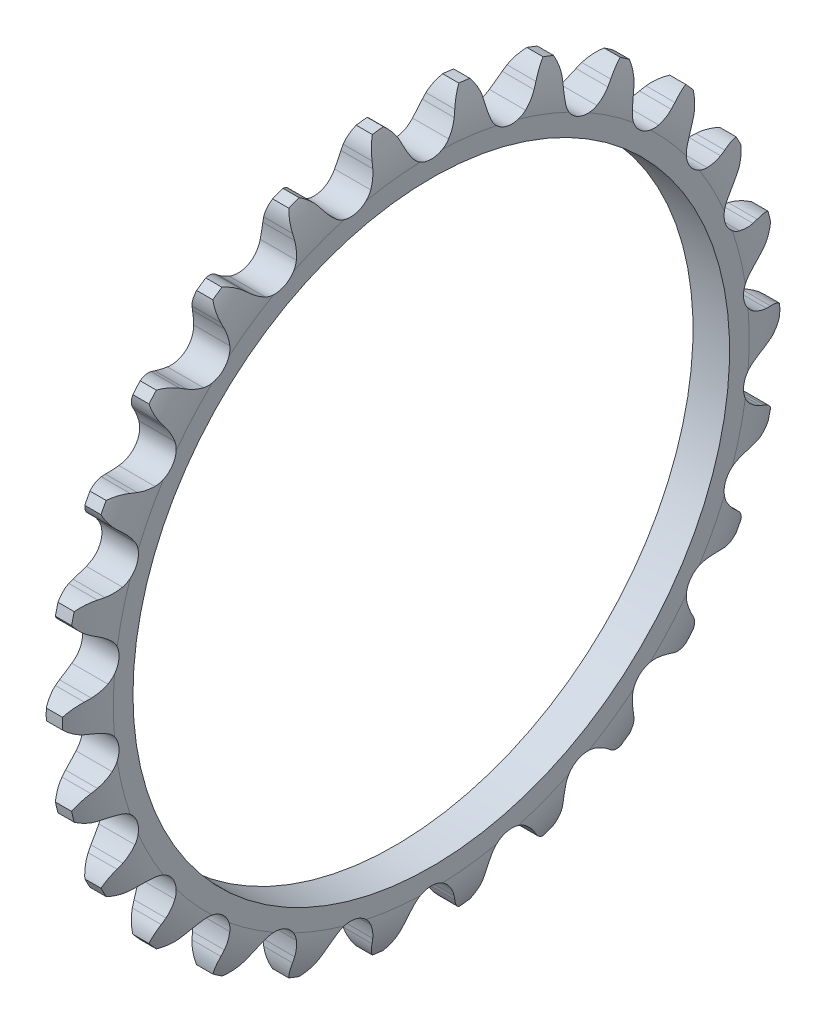
SolidWorks part; units mm, degrees
ref_plane "Plane1" through (0, 0, 0) normal (0, 0, 1) x (1, 0, 0)
ref_plane "Plane2" through (0, 0, 0) normal (0, 1, 0) x (1, 0, 0)
ref_plane "Plane3" through (0, 0, 0) normal (1, 0, 0) x (0, 0, -1)
other "Configuration Table"
sketch "Clipboard" plane through (0, 0, 0) normal (0, 1, 0) x (1, 0, 0)
  line L0 (0, 0) -> (8.561, -4.1755)
  line L1 (-15, 0) -> (100, 0) construction
  line L2 (0, 0) -> (-0.7911, 0.8941)
  line L3 (0, 0) -> (-4.4605, 1.7048)
  line L4 (0, 0) -> (4.2919, 2.0933)
  line L5 (0, 0) -> (-47.5972, -17.7524)
  line L6 (0, 0) -> (-3.555, -2.3986)
  line L7 (-0.7911, 0.8941) -> (44.4721, 23.9568)
  line L8 (-76.2, 38.1) -> (-58.1914, 38.1)
  line L9 (-73.2057, 38.5609) -> (-73.0533, 38.5634)
  line L10 (-73.0533, 76.1892) -> (-62.9187, 76.1892)
  circle A0 centre (0, 0) radius 2.54
  circle A1 centre (0, 0) radius 34.0792
  circle A2 centre (0, 0) radius 38.1
  dimension "Dr" = 5.08
  dimension "MHD" = 68.1584
  dimension "Hub_dia" = 76.2
  dimension "Num_teeth" = 26
  dimension "Pitch" = 9.525
  dimension "Width" = 4.7752
  dimension "Chamfer_wid" = 1.1938
  dimension "Chamfer_dep" = 4.7752
  dimension "Overall_len" = 50.8
  dimension "Show_teeth" = 26
  dimension "Thickness" = 4.2885
  dimension "OAL" = 50.8001
  dimension "T_dim" = 18.0086
  dimension "Width_const" = 0.1524
  dimension "Width_factor" = 0.93
  dimension "Num_strands" = 1
  dimension "Transv_pitch" = 10.1346
sketch "BasProSke" plane through (0, 0, 0) normal (0, 1, 0) x (1, 0, 0)
  line L0 (-10, 0) -> (60, 0) construction
  line L1 (0, 0) -> (0, 37.305)
  line L2 (0, 0) -> (4.2885, 0)
  line L3 (4.2885, 0) -> (4.2885, 37.305)
  line L4 (3.0947, 42.0802) -> (1.1938, 42.0802)
  arc A0 (0, 37.305) -> (1.1938, 42.0802) centre (10.1473, 37.305) cw
  arc A1 (4.2885, 37.305) -> (3.0947, 42.0802) centre (-5.8588, 37.305) ccw
  dimension "Thickness" = 4.2885
  dimension "D1" = 10.1473
  dimension "G1" = 1.1938
  dimension "G2" = 1.1938
  dimension "H2" = 4.7752
  dimension "H1" = 4.7752
  dimension "Diameter" = 84.1604
revolve "Base-Revolve" add sketch "BasProSke" angle 360 about L0
sketch "GrvSke" plane through (0, 0, 0) normal (0, 1, 0) x (1, 0, 0)
  line L0 (4.2885, 37.305) -> (4.2885, 34.0792)
  line L1 (4.2885, 34.0792) -> (10.1346, 34.0792)
  line L2 (10.1346, 34.0792) -> (10.1346, 37.305)
  line L3 (3.0947, 42.0802) -> (11.3284, 42.0802)
  line L4 (7.2116, 0) -> (7.2116, 52.07) construction
  line L5 (-10, 0) -> (60, 0) construction
  line L6 (0, 0) -> (35.56, 0) construction
  arc A0 (10.1346, 37.305) -> (11.3284, 42.0802) centre (20.2819, 37.305) cw
  arc A1 (4.2885, 37.305) -> (3.0947, 42.0802) centre (-5.8588, 37.305) ccw
  dimension "G1" = 1.1938
  dimension "H1" = 4.7752
  dimension "Diameter" = 84.1604
  dimension "Grv_diam" = 68.1584
  dimension "Grv_width" = 5.8461
  dimension "Offset" = 7.2116
revolve "Groove" [suppressed] cut sketch "GrvSke" angle 360 about L6
pattern_linear "Grooves" [suppressed]
sketch "TooCutSke" plane through (0, 0, 0) normal (1, 0, 0) x (0, 0, -1)
  line L0 (2.9609, 39.5391) -> (3.2081, 40.1679)
  line L1 (0, 0) -> (0, 107) construction
  line L2 (0, 39.5108) -> (-10, 39.5108) construction
  line L3 (-2.9609, 39.5391) -> (-3.2081, 40.1679)
  arc A0 (2.0607, 37.9405) -> (2.9609, 39.5391) centre (-3.2325, 41.974) ccw
  arc A1 (2.0607, 37.9405) -> (-2.0607, 37.9405) centre (0, 39.5108) cw
  arc A2 (3.2081, 40.1679) -> (7.0601, 42.7926) centre (7.0601, 38.6535) cw
  arc A3 (-2.0607, 37.9405) -> (-2.9609, 39.5391) centre (3.2325, 41.974) cw
  arc A4 (-3.2081, 40.1679) -> (-7.0601, 42.7926) centre (-7.0601, 38.6535) ccw
  arc A5 (7.0601, 42.7926) -> (-7.0601, 42.7926) centre (0, 0) ccw
  dimension "R" = 2.5908
  dimension "E" = 6.6548
  dimension "F" = 4.139
  dimension "Pitch_radius" = 39.5108
  dimension "W" = 7.0601
  dimension "V" = 0.8573
  dimension "A" = 37.308
  dimension "B" = 15.846
extrude "ToothCut" cut sketch "TooCutSke" along normal through all
pattern_circular "TeethCuts" count 26 every 13.846 about axis through (-10, 0, 0) along (1, 0, 0) of "ToothCut"
sketch "HubNeaOneSke" plane through (0, 0, 0) normal (-1, 0, 0) x (0, 0, 1)
  circle A0 centre (0, 0) radius 34.0792
  dimension "Diameter" = 68.1584
extrude "HubNearOne" [suppressed] add sketch "HubNeaOneSke" along normal blind 46.5115
sketch "HubNeaBotSke" plane through (0, 0, 0) normal (-1, 0, 0) x (0, 0, 1)
  circle A0 centre (0, 0) radius 34.0792
  dimension "Diameter" = 68.1584
extrude "HubNearBoth" [suppressed] add sketch "HubNeaBotSke" along normal blind 23.2558
ref_plane "FarPln" through (4.2885, 0, 0) normal (1, 0, 0) x (0, 0, -1)
sketch "HubFarSke" plane through (4.2885, 0, 0) normal (1, 0, 0) x (0, 0, -1)
  circle A0 centre (0, 0) radius 34.0792
  dimension "Diameter" = 68.1584
extrude "HubFar" [suppressed] add sketch "HubFarSke" along normal blind 23.2558
sketch "BorSke" plane through (0, 0, 0) normal (1, 0, 0) x (0, 0, -1)
  circle A0 centre (0, 0) radius 7.9375
  dimension "Diameter" = 15.875
extrude "Bore" cut sketch "BorSke" along normal mid plane 101.6001
sketch "KeySke" plane through (0, 0, 0) normal (1, 0, 0) x (0, 0, -1)
  line L0 (-2.3813, 0) -> (-2.3813, 10.0711)
  line L1 (-2.3813, 10.0711) -> (2.3813, 10.0711)
  line L2 (2.3813, 10.0711) -> (2.3813, 0)
  line L3 (0, 0) -> (0, 34) construction
  line L4 (-2.3813, 0) -> (2.3813, 0)
  dimension "Offset" = 10.0711
  dimension "Width" = 4.7625
extrude "Keyway" [suppressed] cut sketch "KeySke" along normal mid plane 101.6001
pattern_circular "Keyway2" [suppressed] count 2 every 90 about axis through (-10, 0, 0) along (1, 0, 0)
sketch "Sketch2" plane through (0, 0, 0) normal (-1, 0, 0) x (0, 0, 1)
  circle A0 centre (0, 0) radius 35
  dimension "D1" = 70
extrude "Cut-Extrude1" cut sketch "Sketch2" against normal through all
equation "\"Num_teeth@Clipboard\" = int( \"Num_teeth@Clipboard\" )"
equation "\"Num_teeth@Clipboard\" = ((sgn( \"Num_teeth@Clipboard\" - 5.0)+1)*( \"Num_teeth@Clipboard\" - 5.0))/2 +5.0"
equation "\"Num_teeth@Clipboard\" = ((sgn( \"Num_teeth@Clipboard\" - 200.0)-1)*( \"Num_teeth@Clipboard\" - 200.0))/-2 +200.0"
equation "\"MHD@Clipboard\" = \"Pitch@Clipboard\" * (1.0 / tan(3.14159265 / \"Num_teeth@Clipboard\" ) - 1.0) - 0.03"
equation "\"Thickness@Clipboard\"  = \"Width@Clipboard\" * \"Width_factor@Clipboard\" - \"Width_const@Clipboard\" + (\"Num_strands@Clipboard\" - 1) * \"Transv_pitch@Clipboard\""
equation "\"OAL@Clipboard\" = \"Thickness@Clipboard\""
equation "\"MHD@Clipboard\" = ((sgn( \"MHD@Clipboard\" - \"Hub_dia@Clipboard\" )-1)*( \"MHD@Clipboard\" - \"Hub_dia@Clipboard\" ))/-2+ \"Hub_dia@Clipboard\""
equation "\"OAL@Clipboard\" = ((sgn( \"OAL@Clipboard\" - \"Overall_len@Clipboard\" )+1)*( \"OAL@Clipboard\" - \"Overall_len@Clipboard\" ))/2 + \"Overall_len@Clipboard\" + 0.000002"
equation "\"Num_teeth@TeethCuts\" = int( \"Show_teeth@Clipboard\" ) + 1"
equation "\"Num_teeth@TeethCuts\" = ((sgn( \"Num_teeth@TeethCuts\" - \"Num_teeth@Clipboard\" )-1)*( \"Num_teeth@TeethCuts\" - \"Num_teeth@Clipboard\" ))/-2+ \"Num_teeth@Clipboard\""
equation "\"Num_teeth@TeethCuts\" = ((sgn( \"Num_teeth@TeethCuts\" - 2.0)+1)*( \"Num_teeth@TeethCuts\" - 2.0))/2 +2.0"
equation "\"Angle@TeethCuts\" = 360.0 / \"Num_teeth@Clipboard\""
equation "\"Pitch_radius@TooCutSke\" = ( \"Pitch@Clipboard\" / 2.0) / sin(3.14159265 / \"Num_teeth@Clipboard\" )  'ma"
equation "\"R@TooCutSke\"  = \"Dr@Clipboard\" * 0.5025 + 0.0015"
equation "\"A@TooCutSke\" = 35.0 + (60.0 / \"Num_teeth@Clipboard\")"
equation "\"E@TooCutSke\"  = \"Dr@Clipboard\" * 1.3025 + 0.0015"
equation "\"B@TooCutSke\"  = 18.0 - (56.0 / \"Num_teeth@Clipboard\" )"
equation "\"W@TooCutSke\" = 1.4 * \"Dr@Clipboard\" * cos(3.14159265 / \"Num_teeth@Clipboard\" )"
equation "\"V@TooCutSke\" = 1.4 * \"Dr@Clipboard\" * sin(3.14159265 / \"Num_teeth@Clipboard\" )"
equation "\"Diameter@BasProSke\" = 2.0 * ( (0.3 * \"Pitch@Clipboard\" ) +  \"Pitch@Clipboard\" / 2.0 / tan(3.14159265 / \"Num_teeth@Clipboard\" ))"
equation "\"Thickness@BasProSke\"  = \"Thickness@Clipboard\""
equation "\"G1@BasProSke\" =  \"Chamfer_wid@Clipboard\""
equation "\"G2@BasProSke\" =  \"Chamfer_wid@Clipboard\""
equation "\"H1@BasProSke\" =  \"Chamfer_dep@Clipboard\""
equation "\"H2@BasProSke\" =  \"Chamfer_dep@Clipboard\""
equation "\"Diameter@GrvSke\" = \"Diameter@BasProSke\""
equation "\"G1@GrvSke\" = \"Chamfer_wid@Clipboard\""
equation "\"H1@GrvSke\" = \"Chamfer_dep@Clipboard\""
equation "\"Grv_diam@GrvSke\" =  \"Pitch@Clipboard\" * (1.0 / tan(3.14159265 / \"Num_teeth@Clipboard\" ) - 1.0) - 0.03"
equation "\"Grv_width@GrvSke\" =  \"Transv_pitch@Clipboard\" - ( \"Width@Clipboard\" * \"Width_factor@Clipboard\" - \"Width_const@Clipboard\" )"
equation "\"Offset@GrvSke\" = \"Grv_width@GrvSke\" / 2.0 + ( \"Width@Clipboard\" * \"Width_factor@Clipboard\" - \"Width_const@Clipboard\" )"
equation "\"Offset@Grooves\" = \"Transv_pitch@Clipboard\""
equation "\"Num_grvs@Grooves\" = \"Num_strands@Clipboard\""
equation "\"Num_grvs@Grooves\" = \"Num_grvs@Grooves\" - 1 * sgn( \"Num_grvs@Grooves\" -1)"
equation "\"Diameter@HubNeaOneSke\" = \"MHD@Clipboard\""
equation "\"Length@HubNearOne\" = \"OAL@Clipboard\" - \"Thickness@BasProSke\""
equation "\"Diameter@HubNeaBotSke\" = \"MHD@Clipboard\""
equation "\"Length@HubNearBoth\" = ( \"OAL@Clipboard\" - \"Thickness@BasProSke\" ) / 2.0"
equation "\"Thickness@FarPln\" = \"Thickness@BasProSke\""
equation "\"Diameter@HubFarSke\" = \"MHD@Clipboard\""
equation "\"Length@HubFar\" = ( \"OAL@Clipboard\" - \"Thickness@BasProSke\" ) / 2.0"
equation "\"D1@Bore\" = \"OAL@Clipboard\" * 2.0"
equation "\"D1@Keyway\" = \"OAL@Clipboard\" * 2.0"
equation "\"Offset@KeySke\" = \"T_dim@Clipboard\" - \"Diameter@BorSke\" / 2.0"
